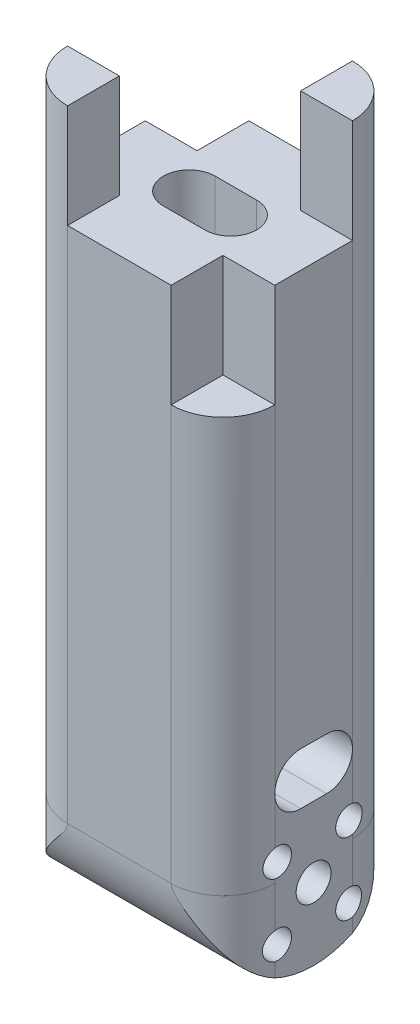
SolidWorks part; units mm, degrees
ref_plane "Plan de face" through (0, 0, 0) normal (0, 0, 1) x (1, 0, 0)
ref_plane "Plan de dessus" through (0, 0, 0) normal (0, 1, 0) x (1, 0, 0)
ref_plane "Plan de droite" through (0, 0, 0) normal (1, 0, 0) x (0, 0, -1)
sketch "Esquisse3" plane through (0, 0, 0) normal (0, 1, 0) x (1, 0, 0)
  line L1 (-20, -17.5) -> (20, -17.5)
  line L2 (-20, -17.5) -> (-20, 17.5)
  line L3 (-20, 17.5) -> (20, 17.5)
  line L4 (20, -17.5) -> (20, 17.5)
  line L5 (-20, -17.5) -> (20, 17.5) construction
  line L6 (-20, 17.5) -> (20, -17.5) construction
  point P0 (0, 0)
  dimension "D1" = 40
  dimension "D2" = 35
extrude "Boss.-Extru.2" add sketch "Esquisse3" along normal blind 120
fillet "Congé1" radius 10 4 edges at (-20, 60, -17.5) (-20, 60, 17.5) (20, 60, -17.5) (20, 60, 17.5)
sketch "Esquisse4" plane through (0, 120, 0) normal (0, 1, 0) x (1, 0, 0)
  line L0 (-10, 17.5) -> (10, 17.5)
  line L1 (10, 17.5) -> (10, 7.5)
  line L2 (10, 7.5) -> (20, 7.5)
  line L3 (20, 7.5) -> (20, -17.5)
  line L4 (20, -17.5) -> (-10, -17.5)
  line L5 (-10, -17.5) -> (-10, -7.5)
  line L6 (-10, -7.5) -> (-20, -7.5)
  line L7 (-20, -7.5) -> (-20, 17.5)
  line L8 (-20, 17.5) -> (-10, 17.5)
  line L9 (-10, -17.5) -> (10, -17.5) construction
extrude "Enlèv. mat.-Extru.1" cut sketch "Esquisse4" against normal blind 20
sketch "Esquisse5" plane through (0, 100, 0) normal (0, 1, 0) x (1, 0, 0)
  line L1 (-20, 7.5) -> (-10, 7.5)
  line L2 (-20, 7.5) -> (-20, 17.5)
  line L3 (-20, 17.5) -> (-10, 17.5)
  line L4 (-10, 7.5) -> (-10, 17.5)
  line L5 (10, -17.5) -> (20, -17.5)
  line L6 (10, -17.5) -> (10, -7.5)
  line L7 (10, -7.5) -> (20, -7.5)
  line L8 (20, -17.5) -> (20, -7.5)
extrude "Enlèv. mat.-Extru.2" cut sketch "Esquisse5" against normal blind 20
sketch "Esquisse6" plane through (0, 100, 0) normal (0, 1, 0) x (1, 0, 0)
  line L0 (-4, 0) -> (4, 0) construction
  line L1 (-4, 5) -> (4, 5)
  line L2 (-4, -5) -> (4, -5)
  arc A0 (-4, 5) -> (-4, -5) centre (-4, 0) ccw
  arc A1 (4, -5) -> (4, 5) centre (4, 0) ccw
  point P2 (0, 0)
  dimension "D2" = 5
  dimension "D1" = 8
extrude "Enlèv. mat.-Extru.3" cut sketch "Esquisse6" against normal blind 90
sketch "Esquisse8" plane through (-20, 0, 0) normal (-1, 0, 0) x (0, 0, 1)
  line L0 (-7.5, 0) -> (7.5, 0) construction
  line L1 (17.5, 100) -> (17.5, 0) construction
  line L2 (-17.5, 0) -> (17.5, 0)
  arc A0 (-17.5, 0) -> (17.5, 0) centre (0, 0) ccw
extrude "Boss.-Extru.3" add sketch "Esquisse8" against normal blind 40
sketch "Esquisse9" plane through (0, 0, 0) normal (0, 1, 0) x (1, 0, 0)
  line L0 (-10, 17.5) -> (-20, 17.5)
  line L1 (-20, 17.5) -> (-20, 7.5)
  line L2 (10, 17.5) -> (20, 17.5)
  line L3 (20, 17.5) -> (20, 7.5)
  line L4 (-20, -7.5) -> (-20, -17.5)
  line L5 (-20, -17.5) -> (-10, -17.5)
  line L6 (10, -17.5) -> (20, -17.5)
  line L7 (20, -17.5) -> (20, -7.5)
  arc A0 (-10, 17.5) -> (-20, 7.5) centre (-10, 7.5) ccw construction
  arc A1 (20, 7.5) -> (10, 17.5) centre (10, 7.5) ccw construction
  arc A2 (-20, -7.5) -> (-10, -17.5) centre (-10, -7.5) ccw construction
  arc A3 (10, -17.5) -> (20, -7.5) centre (10, -7.5) ccw construction
  spline S0 degree 2 poles (-20, 7.5) (-19.1421, 16.6421) (-10, 17.5) knots 0 0 0 1 1 1
  spline S1 degree 2 poles (10, 17.5) (19.1421, 16.6421) (20, 7.5) knots 0 0 0 1 1 1
  spline S2 degree 2 poles (-20, -7.5) (-19.1421, -16.6421) (-10, -17.5) knots 0 0 0 1 1 1
  spline S3 degree 2 poles (20, -7.5) (19.1421, -16.6421) (10, -17.5) knots 0 0 0 1 1 1
extrude "Enlèv. mat.-Extru.4" cut sketch "Esquisse9" against normal blind 60
sketch "Esquisse10" plane through (0, 0, 0) normal (0, 1, 0) x (1, 0, 0)
  line L1 (-9.75, -10.55) -> (-2.55, -10.55)
  line L2 (-9.75, -10.55) -> (-9.75, 10.55)
  line L3 (-9.75, 10.55) -> (-2.55, 10.55)
  line L4 (-2.55, -10.55) -> (-2.55, 10.55)
  line L5 (2.55, -10.55) -> (9.75, -10.55)
  line L6 (2.55, -10.55) -> (2.55, 10.55)
  line L7 (2.55, 10.55) -> (9.75, 10.55)
  line L8 (9.75, -10.55) -> (9.75, 10.55)
  dimension "D1" = 7.2
  dimension "D2" = 7.2
  dimension "D3" = 21.1
  dimension "D4" = 21.1
  dimension "D5" = 2.55
  dimension "D6" = 2.55
  dimension "D7" = 10.55
extrude "Enlèv. mat.-Extru.5" cut sketch "Esquisse10" against normal through all and the other way blind 6.8
sketch "Esquisse11" plane through (20, 0, 0) normal (1, 0, 0) x (0, 0, -1)
  line L0 (-2.5, 15) -> (2.5, 15) construction
  line L1 (-2.5, 20) -> (2.5, 20)
  line L2 (-2.5, 10) -> (2.5, 10)
  line L3 (7.5, 0) -> (14.5711, 0) construction
  arc A0 (-2.5, 20) -> (-2.5, 10) centre (-2.5, 15) ccw
  arc A1 (2.5, 10) -> (2.5, 20) centre (2.5, 15) ccw
  point P2 (0, 15)
  point P7 (0, 0)
  dimension "D2" = 5
  dimension "D1" = 5
  dimension "D3" = 10
extrude "Enlèv. mat.-Extru.6" cut sketch "Esquisse11" against normal through all
sketch "Esquisse12" plane through (2.55, 0, 0) normal (1, 0, 0) x (0, 0, -1)
  line L0 (-10.55, -13.9624) -> (10.55, -13.9624) construction
  line L1 (6.5, -40.1276) -> (-6.5, -40.1276)
  line L2 (6.5, -40.1276) -> (6.5, 5.1276)
  line L3 (6.5, 5.1276) -> (-6.5, 5.1276)
  line L4 (-6.5, -40.1276) -> (-6.5, 5.1276)
  line L5 (6.5, -40.1276) -> (-6.5, 5.1276) construction
  line L6 (6.5, 5.1276) -> (-6.5, -40.1276) construction
  arc A0 (-10.55, -13.9624) -> (10.55, -13.9624) centre (0, 0) ccw construction
  point P0 (0, -17.5)
  dimension "D1" = 13
  dimension "D2" = 19.09
extrude "Enlèv. mat.-Extru.7" cut sketch "Esquisse12" against normal blind 6
hole_wizard "Trous de centrage Ø1.0mm1" positions "Esquisse13" profile "Esquisse14" hole size "Ø1.0" standard "Ansi Metric" end condition through all
sketch "Esquisse13" plane through (20, 0, 0) normal (1, 0, 0) x (0, 0, -1)
  arc A1 (-7.5, -15.8114) -> (7.5, -15.8114) centre (0, 0) ccw construction
  point P0 (0, -3.6)
  point P10 (0, -17.5)
  dimension "D1" = 13.9
sketch "Esquisse14" plane through (20, -3.6, 0) normal (0, 1, 0) x (0, 0, -1)
  line L0 (0, 0) -> (0, 40)
  line L1 (0, 40) -> (3.3734, 40)
  line L2 (3.3734, 40) -> (3.3734, 0)
  line L5 (3.3734, 0) -> (0, 0)
  line L11 (0, -6.35) -> (0, 107.95) construction
  dimension "Diamètre du perçage jusqu'au prochain" = 6.7469
  dimension "Profondeur du perçage jusqu'au prochain" = 40
hole_wizard "Dégagement M51" positions "Esquisse15" profile "Esquisse16" hole size "M5" standard "Ansi Metric"
sketch "Esquisse15" plane through (-20, 0, 0) normal (-1, 0, 0) x (0, 0, 1)
  circle A0 centre (0, -3.6) radius 3.3734 construction
  point P0 (-6.915, -10.515)
  point P2 (-6.915, 3.315)
  point P4 (6.915, 3.315)
  point P6 (6.915, -10.515)
  point P15 (-6.915, -9.9436)
  point P16 (7.5, -19.0794)
  point P17 (0, 0)
  point P18 (0, 0)
  dimension "D6" = 6.915
  dimension "D1" = 13.83
  dimension "D2" = 13.83
  dimension "D3" = 13.83
  dimension "D4" = 13.83
  dimension "D5" = 6.915
sketch "Esquisse16" plane through (-20, -10.515, -6.915) normal (0, 1, 0) x (0, 0, 1)
  line L0 (0, 0) -> (0, 13.6524)
  line L1 (0, 13.6524) -> (2.75, 12)
  line L2 (2.75, 12) -> (2.75, 0)
  line L5 (2.75, 0) -> (0, 0)
  line L10 (0, 13.6524) -> (-2.75, 12) construction
  line L11 (0, -6.35) -> (0, 107.95) construction
  dimension "Diamètre du perçage" = 5.5
  dimension "Profondeur du perçage" = 12
  dimension "Angle de pointe" = 118
hole_wizard "Dégagement M52" positions "Esquisse19" profile "Esquisse20" hole size "M5" standard "Ansi Metric"
sketch "Esquisse19" plane through (20, 0, 0) normal (1, 0, 0) x (0, 0, -1)
  circle A0 centre (0, -3.6) radius 3.3734 construction
  point P0 (-6.915, -10.515)
  point P2 (6.915, -10.515)
  point P4 (6.915, 3.315)
  point P6 (-6.915, 3.315)
  point P9 (0, 0)
  point P10 (0, 0)
  point P11 (0, 0)
  point P12 (0, 0)
  point P19 (8.3583, -10.515)
  dimension "D4" = 6.915
  dimension "D1" = 13.83
  dimension "D2" = 13.83
  dimension "D3" = 6.915
sketch "Esquisse20" plane through (20, -10.515, 6.915) normal (0, 1, 0) x (0, 0, -1)
  line L0 (0, 0) -> (0, 13.5923)
  line L1 (0, 13.5923) -> (2.65, 12)
  line L2 (2.65, 12) -> (2.65, 0)
  line L5 (2.65, 0) -> (0, 0)
  line L10 (0, 13.5923) -> (-2.65, 12) construction
  line L11 (0, -6.35) -> (0, 107.95) construction
  dimension "Diamètre du perçage" = 5.3
  dimension "Profondeur du perçage" = 12
  dimension "Angle de pointe" = 118
